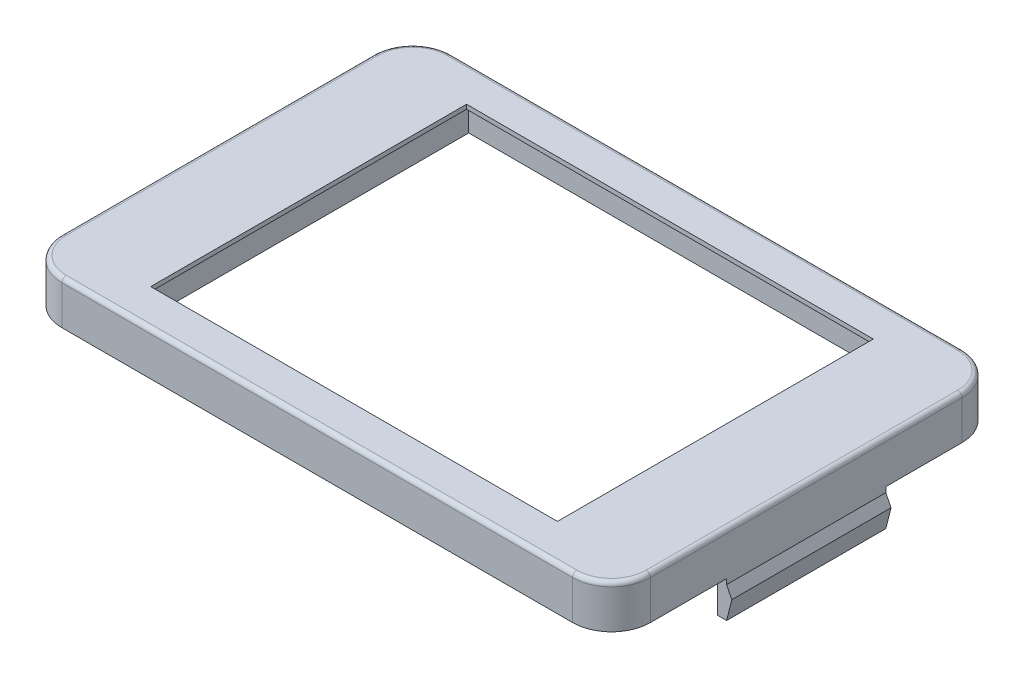
SolidWorks part; units mm, degrees
ref_plane "Front Plane" through (0, 0, 0) normal (0, 0, 1) x (1, 0, 0)
ref_plane "Top Plane" through (0, 0, 0) normal (0, 1, 0) x (1, 0, 0)
ref_plane "Right Plane" through (0, 0, 0) normal (1, 0, 0) x (0, 0, -1)
sketch "Sketch1" plane through (0, 0, 0) normal (0, 1, 0) x (1, 0, 0)
  line L0 (-88.0364, 0) -> (81, 0) construction
  line L1 (-34, 22.5) -> (34, 22.5)
  line L2 (-34, 22.5) -> (-34, -22.5)
  line L3 (-34, -22.5) -> (34, -22.5)
  line L4 (34, 22.5) -> (34, -22.5)
  line L5 (0, 54.5727) -> (0, -40.8273) construction
  line L7 (-23.5, 18.25) -> (23.5, 18.25)
  line L8 (-23.5, 18.25) -> (-23.5, -18.25)
  line L9 (-23.5, -18.25) -> (23.5, -18.25)
  line L10 (23.5, 18.25) -> (23.5, -18.25)
  dimension "D1" = 45
  dimension "D2" = 68
  dimension "D3" = 36.5
  dimension "D4" = 47
extrude "Boss-Extrude1" add sketch "Sketch1" along normal blind 5
sketch "Sketch2" plane through (0, 0, 0) normal (0, -1, 0) x (1, 0, 0)
  line L0 (-45.003, 0) -> (44.8346, 0) construction
  line L1 (-25.5, 20.5) -> (30.5, 20.5)
  line L2 (-25.5, 20.5) -> (-25.5, -20.5)
  line L3 (-25.5, -20.5) -> (30.5, -20.5)
  line L4 (30.5, 20.5) -> (30.5, -20.5)
  line L5 (2.5, 25.2791) -> (2.5, -25.0546) construction
  dimension "D1" = 56
  dimension "D2" = 41
  dimension "D3" = 2.5
extrude "Cut-Extrude1" cut sketch "Sketch2" against normal offset from surface (4.5 mm away) 0.5 up to face at (0, 5, 0)
sketch "Sketch3" plane through (0, 0, 0) normal (0, 0, 1) x (1, 0, 0)
  line L0 (30.5, 4.5) -> (32.9538, 0)
  line L1 (-34, 0) -> (34, 0) construction
  line L2 (32.9538, 0) -> (30.5, 0)
  line L3 (30.5, 0) -> (30.5, 4.5)
extrude "Cut-Extrude2" cut sketch "Sketch3" against normal blind 18.5 and the other way blind 18.5
fillet "Fillet1" radius 4.5 4 edges at (-34, 2.5, -22.5) (-34, 2.5, 22.5) (34, 2.5, -22.5) (34, 2.5, 22.5)
fillet "Fillet2" radius 0.5 8 edges at (-32.682, 5, 21.182) (-34, 5, 0) (-32.682, 5, -21.182) (32.682, 5, -21.182) (0, 5, -22.5) (34, 5, 0) (32.682, 5, 21.182) (0, 5, 22.5)
sketch "Sketch4" plane through (0, 0, 0) normal (0, -1, 0) x (1, 0, 0)
  line L0 (-40.4295, 0) -> (42.7674, 0) construction
  line L1 (32.9538, 18.5) -> (32.9538, -18.5) construction
  line L2 (32.9538, 9.2) -> (34, 9.2)
  line L3 (32.9538, 9.2) -> (32.9538, -9.2)
  line L4 (32.9538, -9.2) -> (34, -9.2)
  line L5 (34, 9.2) -> (34, -9.2)
  line L6 (34, 18) -> (34, -18) construction
  dimension "D1" = 18.4
extrude "Boss-Extrude2" add sketch "Sketch4" along normal blind 4.2
sketch "Sketch5" plane through (0, 0, -9.2) normal (0, 0, -1) x (-1, 0, 0)
  line L0 (-34, -0.6) -> (-34.6, -1.8114)
  line L1 (-34, -4.2) -> (-34, 0) construction
  line L2 (-34.6, -1.8114) -> (-34, -4.2)
  line L3 (-34, -4.2) -> (-34, -0.6)
  line L4 (-32.9538, 0) -> (-34, 0) construction
  dimension "D1" = 0.6
  dimension "D2" = 0.6
extrude "Boss-Extrude3" add sketch "Sketch5" against normal up to surface (18.4 mm away) up to face at (33.4769, -2.1, 9.2)
mirror "Mirror1" about plane through (0, 0, 0) normal (1, 0, 0) of "Boss-Extrude3", "Boss-Extrude2"
